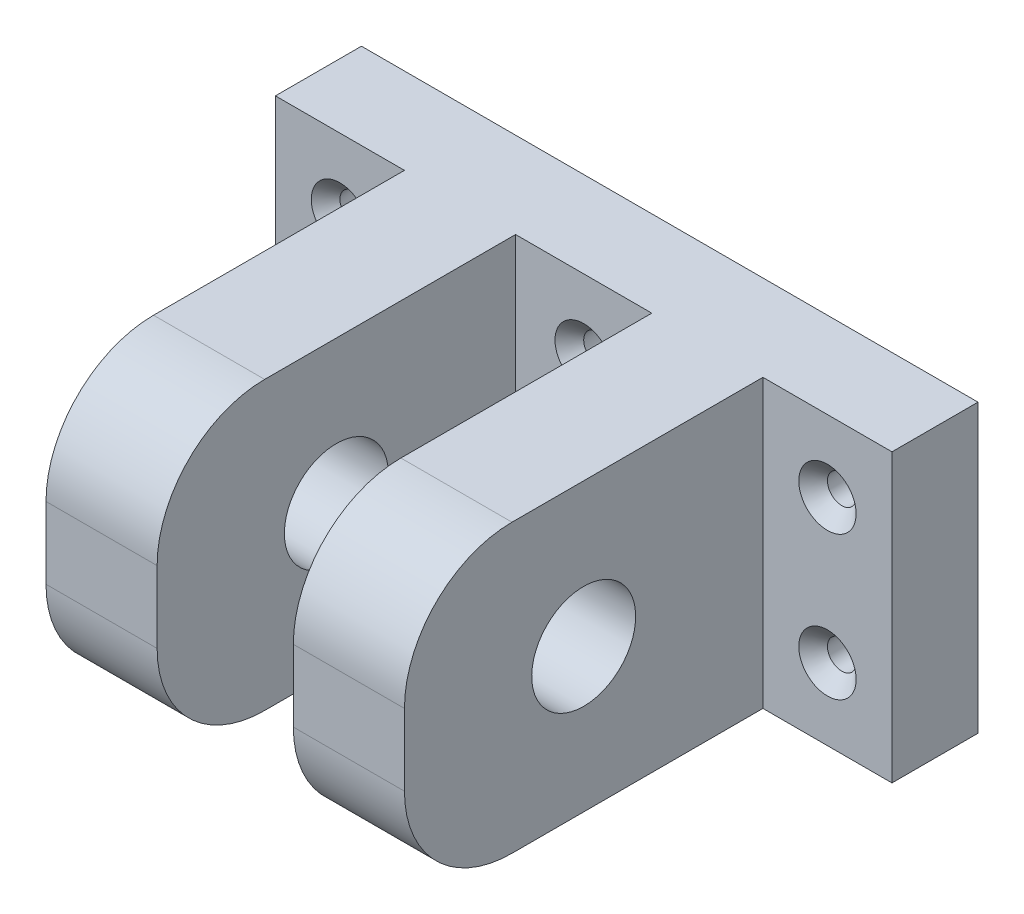
SolidWorks part; units mm, degrees
ref_plane "Front Plane" through (0, 0, 0) normal (0, 0, 1) x (1, 0, 0)
ref_plane "Top Plane" through (0, 0, 0) normal (0, 1, 0) x (1, 0, 0)
ref_plane "Right Plane" through (0, 0, 0) normal (1, 0, 0) x (0, 0, -1)
sketch "Sketch1" plane through (0, 0, 0) normal (0, 0, 1) x (1, 0, 0)
  line L1 (0, 0) -> (86, 0)
  line L2 (0, 0) -> (0, 40)
  line L3 (0, 40) -> (86, 40)
  line L4 (86, 0) -> (86, 40)
  dimension "D1" = 86
  dimension "D2" = 40
extrude "Boss-Extrude1" add sketch "Sketch1" along normal blind 12
sketch "Sketch2" plane through (0, 0, 12) normal (0, 0, 1) x (1, 0, 0)
  line L0 (86, 40) -> (0, 40) construction
  line L1 (18, 40) -> (33.5, 40)
  line L2 (18, 40) -> (18, 0)
  line L3 (18, 0) -> (33.5, 0)
  line L4 (33.5, 40) -> (33.5, 0)
  line L5 (0, 0) -> (86, 0) construction
  line L6 (0, 40) -> (0, 0) construction
  line L7 (52.5, 40) -> (68, 40)
  line L8 (52.5, 40) -> (52.5, 0)
  line L9 (52.5, 0) -> (68, 0)
  line L10 (68, 40) -> (68, 0)
  line L11 (86, 0) -> (86, 40) construction
  dimension "D1" = 15.5
  dimension "D2" = 15.5
  dimension "D3" = 18
  dimension "D4" = 18
extrude "Boss-Extrude2" add sketch "Sketch2" along normal blind 50
sketch "Sketch3" plane through (18, 0, 0) normal (-1, 0, 0) x (0, 0, 1)
  line L0 (62, 40) -> (12, 40) construction
  line L1 (12, 40) -> (12, 0) construction
  circle A0 centre (37, 20) radius 7.25
  dimension "D2" = 25
  dimension "D3" = 14.5
  dimension "D1" = 20
extrude "Cut-Extrude1" cut sketch "Sketch3" against normal blind 50
fillet "Fillet1" radius 15 4 edges at (25.75, 40, 62) (60.25, 40, 62) (25.75, 0, 62) (60.25, 0, 62)
sketch "Sketch5" plane through (0, 0, 12) normal (0, 0, 1) x (1, 0, 0)
  line L0 (18, 40) -> (0, 40) construction
  line L1 (0, 0) -> (18, 0) construction
  line L2 (52.5, 40) -> (33.5, 40) construction
  line L3 (33.5, 0) -> (52.5, 0) construction
  line L4 (68, 0) -> (86, 0) construction
  line L5 (0, 40) -> (0, 0) construction
  line L6 (86, 0) -> (86, 40) construction
  line L7 (86, 40) -> (68, 40) construction
  circle A0 centre (9, 30) radius 2
  circle A1 centre (9, 10) radius 2
  circle A2 centre (43, 30) radius 2
  circle A3 centre (43, 10) radius 2
  circle A4 centre (77, 30) radius 2
  circle A5 centre (77, 10) radius 2
  point P14 (9, 40)
  point P23 (43, 0)
  dimension "D1" = 4
  dimension "D2" = 4
  dimension "D3" = 4
  dimension "D4" = 4
  dimension "D5" = 4
  dimension "D6" = 4
  dimension "D7" = 10
  dimension "D8" = 10
  dimension "D9" = 10
  dimension "D10" = 10
  dimension "D11" = 10
  dimension "D13" = 9
  dimension "D14" = 9
  dimension "D15" = 43
  dimension "D16" = 43
  dimension "D17" = 10
  dimension "D18" = 9
  dimension "D19" = 9
  dimension "D12" = 10
extrude "Cut-Extrude2" cut sketch "Sketch5" against normal blind 50
chamfer "Chamfer1" distance 2 angle 45 6 edges at (79, 10, 12) (79, 30, 12) (45, 10, 12) (45, 30, 12) (11, 10, 12) (11, 30, 12)
sketch "Sketch6" plane through (0, 0, 0) normal (0, 0, -1) x (-1, 0, 0)
  line L0 (0, 40) -> (0, 0) construction
  line L1 (0, 0) -> (-86, 0) construction
  circle A0 centre (-10, 20) radius 3
  circle A1 centre (-40, 20) radius 3
  dimension "D1" = 10
  dimension "D2" = 30
  dimension "D3" = 6
  dimension "D4" = 20
  dimension "D5" = 20
  dimension "D6" = 6
extrude "Cut-Extrude3" cut sketch "Sketch6" against normal blind 10
sketch "Sketch7" plane through (0, 0, 0) normal (0, 0, -1) x (-1, 0, 0)
  circle A0 centre (-10, 20) radius 5
  circle A1 centre (-40, 20) radius 5
  dimension "D1" = 10
  dimension "D2" = 10
extrude "Cut-Extrude4" cut sketch "Sketch7" against normal blind 5
